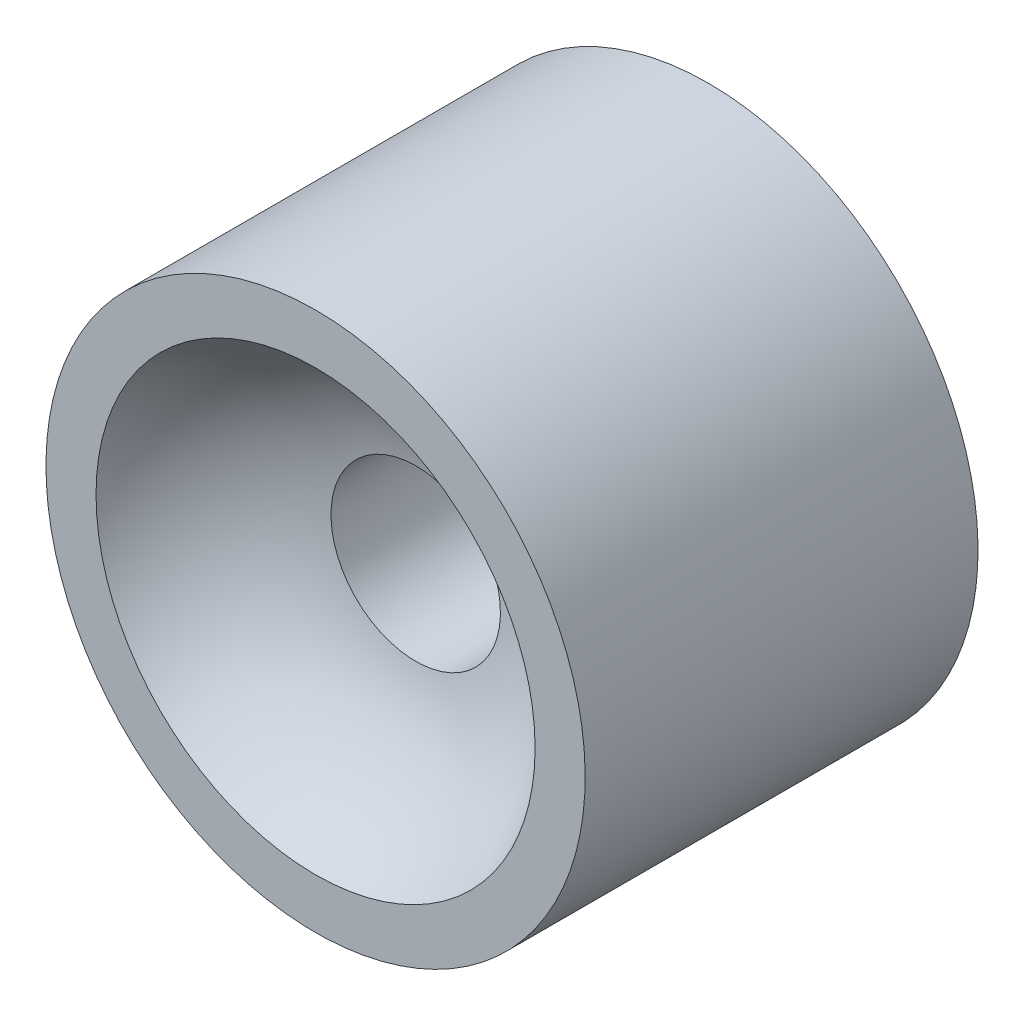
SolidWorks part; units mm, degrees
ref_plane "Front Plane" through (0, 0, 0) normal (0, 0, 1) x (1, 0, 0)
ref_plane "Top Plane" through (0, 0, 0) normal (0, 1, 0) x (1, 0, 0)
ref_plane "Right Plane" through (0, 0, 0) normal (1, 0, 0) x (0, 0, -1)
sketch "Sketch2" plane through (0, 0, 0) normal (1, 0, 0) x (0, 0, -1)
  line L0 (-25.5, 35) -> (25.5, 35)
  line L1 (-12.5, 11) -> (12.5, 11)
  line L2 (12.5, 11) -> (12.5, 0) construction
  line L3 (12.5, 0) -> (-12.5, 0) construction
  line L4 (-12.5, 0) -> (-12.5, 11) construction
  line L5 (0, 11) -> (0, 35) construction
  line L6 (-25.5, 35) -> (-25.5, 28.5)
  line L7 (25.5, 35) -> (25.5, 28.5)
  line L8 (-25.5, 28.5) -> (25.5, 28.5) construction
  arc A0 (-25.5, 28.5) -> (-12.5, 11) centre (-37.0606, 6.3335) cw
  arc A1 (12.5, 11) -> (25.5, 28.5) centre (37.0606, 6.3335) cw
  point P6 (0, 0)
  dimension "D1" = 51
  dimension "D4" = 6.5
  dimension "D6" = 25
  dimension "D2" = 11
  dimension "D3" = 35
  dimension "D5" = 25
revolve "Revolve1" add sketch "Sketch2" angle 360 about L3
ref_plane "Plane1" through (0, 0, 0) normal (0, 0, 1) x (1, 0, 0)
